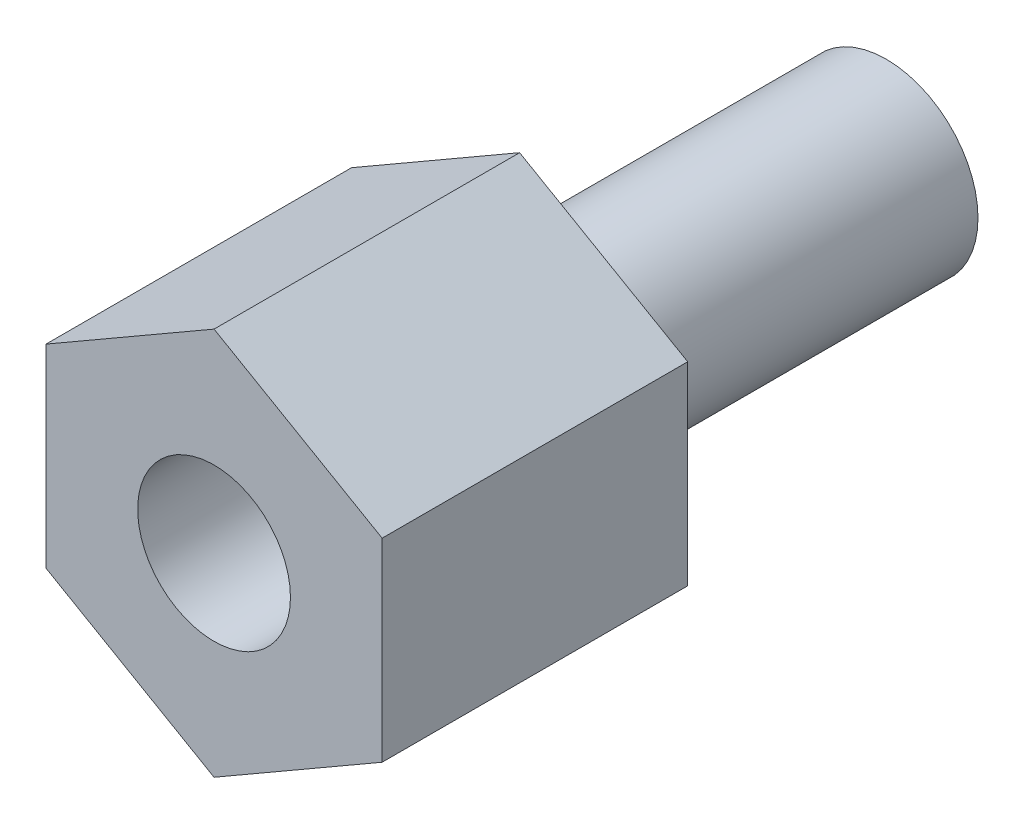
SolidWorks part; units mm, degrees
ref_plane "Front Plane" through (0, 0, 0) normal (0, 0, 1) x (1, 0, 0)
ref_plane "Top Plane" through (0, 0, 0) normal (0, 1, 0) x (1, 0, 0)
ref_plane "Right Plane" through (0, 0, 0) normal (1, 0, 0) x (0, 0, -1)
sketch "SK_hex" plane through (0, 0, 0) normal (0, 0, 1) x (1, 0, 0)
  line L0 (2.75, 1.5877) -> (2.75, -1.5877)
  line L1 (2.75, -1.5877) -> (0, -3.1754)
  line L2 (0, -3.1754) -> (-2.75, -1.5877)
  line L3 (-2.75, -1.5877) -> (-2.75, 1.5877)
  line L4 (-2.75, 1.5877) -> (0, 3.1754)
  line L5 (0, 3.1754) -> (2.75, 1.5877)
extrude "Hex" add sketch "SK_hex" along normal blind 5
sketch "SK_male" plane through (0, 0, 0) normal (0, 0, 1) x (1, 0, 0)
  circle A0 centre (0, 0) radius 1.5
extrude "Male" add sketch "SK_male" against normal blind 6
sketch "SK_female" plane through (0, 0, 0) normal (0, 0, 1) x (1, 0, 0)
  circle A0 centre (0, 0) radius 1.25
extrude "Female" cut sketch "SK_female" along normal through all
